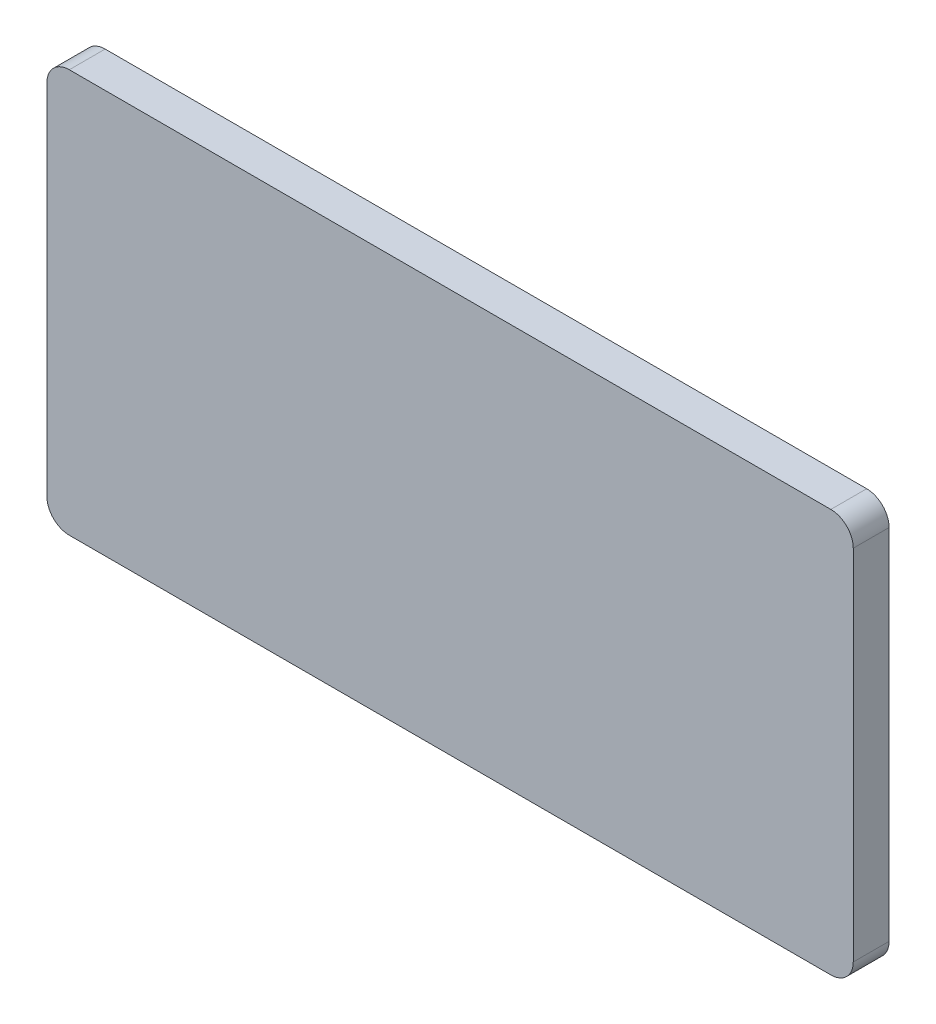
SolidWorks part; units mm, degrees
ref_plane "Front Plane" through (0, 0, 0) normal (0, 0, 1) x (1, 0, 0)
ref_plane "Top Plane" through (0, 0, 0) normal (0, 1, 0) x (1, 0, 0)
ref_plane "Right Plane" through (0, 0, 0) normal (1, 0, 0) x (0, 0, -1)
sketch "Sketch2" plane through (0, 0, 0) normal (0, 0, 1) x (1, 0, 0)
  line L1 (-900, 450) -> (900, 450)
  line L2 (-900, 450) -> (-900, -450)
  line L3 (-900, -450) -> (900, -450)
  line L4 (900, 450) -> (900, -450)
  line L5 (-900, 450) -> (900, -450) construction
  line L6 (-900, -450) -> (900, 450) construction
  point P0 (0, 0)
  dimension "D1" = 1800
  dimension "D2" = 900
extrude "Boss-Extrude1" add sketch "Sketch2" along normal blind 80
fillet "Fillet1" radius 50 4 edges at (900, -450, 40) (-900, -450, 40) (-900, 450, 40) (900, 450, 40)
